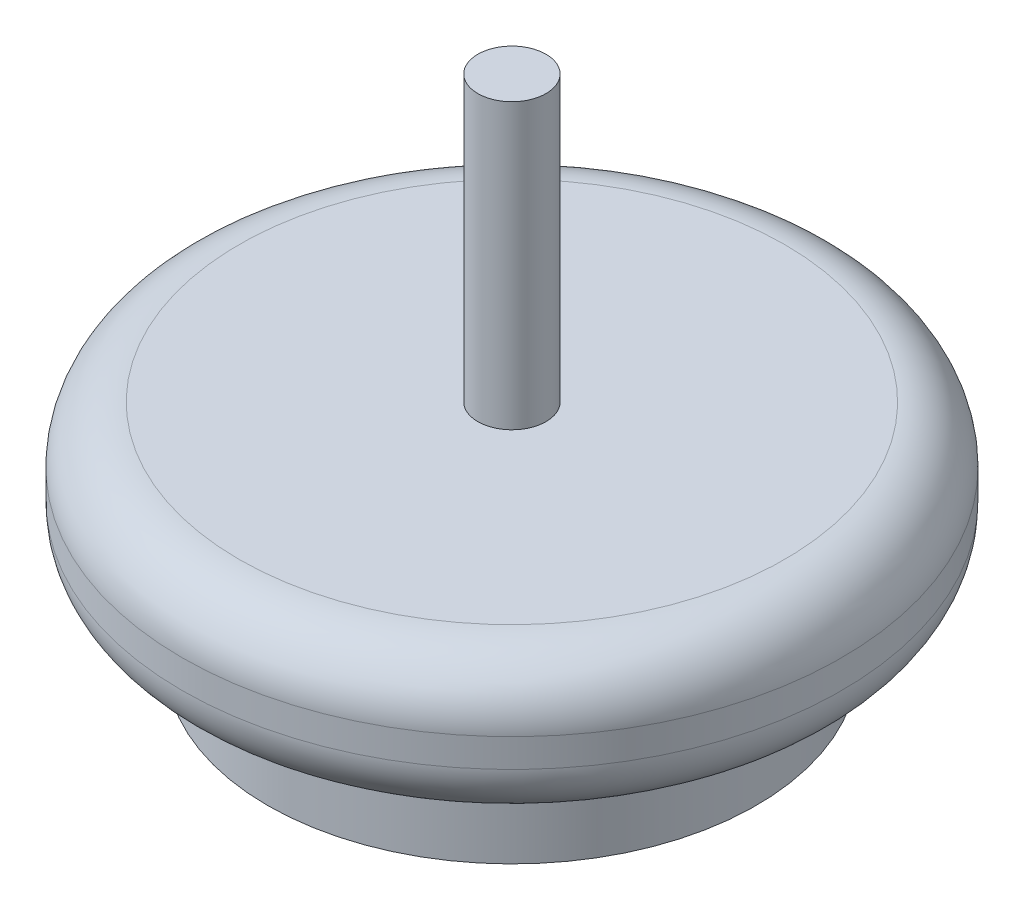
SolidWorks part; units mm, degrees
ref_plane "Front Plane" through (0, 0, 0) normal (0, 0, 1) x (1, 0, 0)
ref_plane "Top Plane" through (0, 0, 0) normal (0, 1, 0) x (1, 0, 0)
ref_plane "Right Plane" through (0, 0, 0) normal (1, 0, 0) x (0, 0, -1)
sketch "Sketch1" plane through (0, 0, 0) normal (0, 1, 0) x (1, 0, 0)
  circle A0 centre (0, 0) radius 58
  dimension "D1" = 116
extrude "Boss-Extrude1" add sketch "Sketch1" along normal blind 25
sketch "Sketch2" plane through (0, 0, 0) normal (0, 1, 0) x (1, 0, 0)
  circle A0 centre (0, 0) radius 43
  circle A1 centre (0, 0) radius 58 construction
  dimension "D1" = 15
extrude "Boss-Extrude2" add sketch "Sketch2" against normal blind 15
fillet "Fillet1" radius 10 2 edges at (0, 25, 58) (0, 0, 58)
sketch "Sketch3" plane through (0, 0, 0) normal (0, 1, 0) x (1, 0, 0)
  circle A0 centre (0, 0) radius 6
  dimension "D1" = 12
extrude "Boss-Extrude3" add sketch "Sketch3" along normal blind 50 from surface at 25 starting at face at (0, 25, 48)
